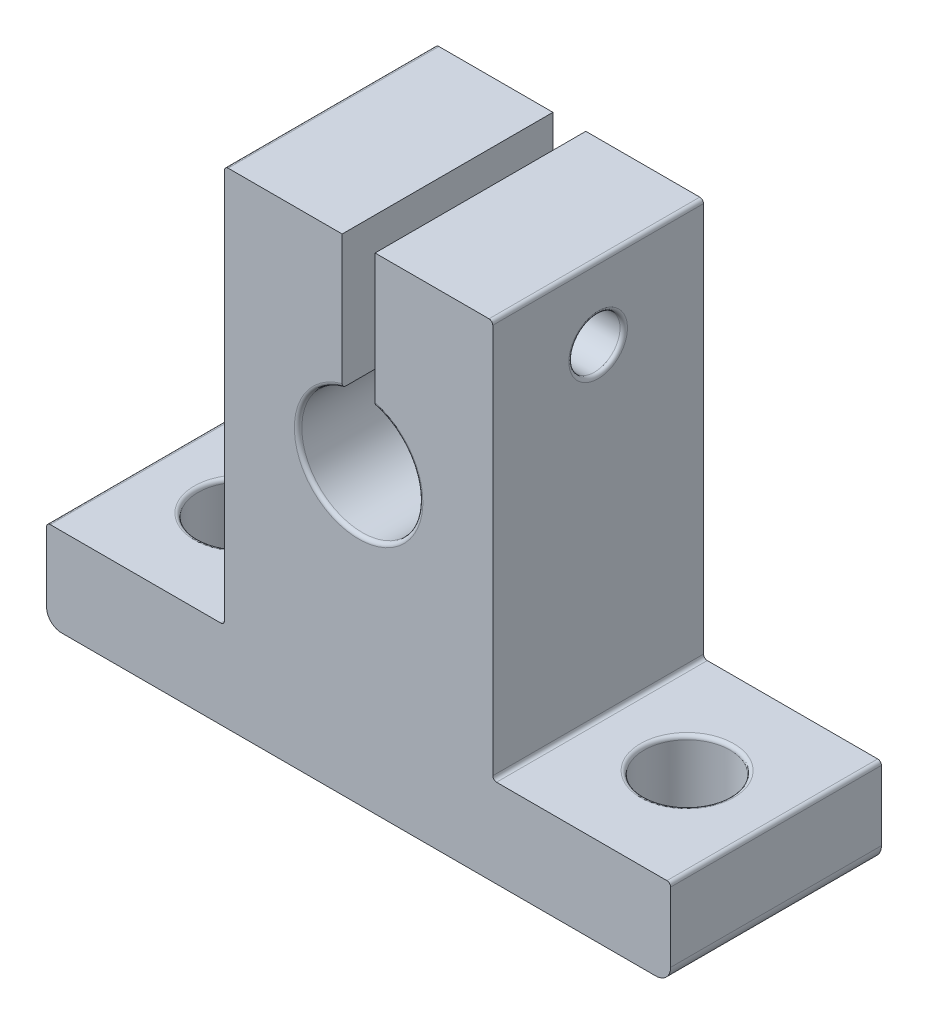
SolidWorks part; units mm, degrees
ref_plane "Front Plane" through (0, 0, 0) normal (0, 0, 1) x (1, 0, 0)
ref_plane "Top Plane" through (0, 0, 0) normal (0, 1, 0) x (1, 0, 0)
ref_plane "Right Plane" through (0, 0, 0) normal (1, 0, 0) x (0, 0, -1)
sketch "Sketch1" plane through (0, 0, 0) normal (0, 0, 1) x (1, 0, 0)
  line L0 (-20.875, 0) -> (20.875, 0)
  line L1 (20.875, 0) -> (20.875, 5.9)
  line L2 (20.875, 5.9) -> (8.975, 5.9)
  line L3 (8.975, 5.9) -> (8.975, 32.5)
  line L4 (8.975, 32.5) -> (1.1, 32.5)
  line L5 (1.1, 32.5) -> (1.1, 23.5728)
  line L6 (0, 0) -> (0, 19.675) construction
  line L7 (-1.1, 32.5) -> (-1.1, 23.5728)
  line L8 (-8.975, 32.5) -> (-1.1, 32.5)
  line L9 (-8.975, 5.9) -> (-8.975, 32.5)
  line L10 (-20.875, 5.9) -> (-8.975, 5.9)
  line L11 (-20.875, 0) -> (-20.875, 5.9)
  arc A0 (-1.1, 23.5728) -> (1.1, 23.5728) centre (0, 19.675) ccw
  dimension "D7" = 11.9
  dimension "D5" = 4.05
  dimension "D1" = 20.875
  dimension "D2" = 5.9
  dimension "D3" = 32.5
  dimension "D4" = 7.875
  dimension "D6" = 19.675
  dimension "D8" = 8.9272
  dimension "D9" = 1.1
extrude "Boss-Extrude1" add sketch "Sketch1" along normal mid plane 14.1
sketch "Sketch2" plane through (0, 5.9, 0) normal (0, 1, 0) x (1, 0, 0)
  line L0 (20.875, 0) -> (14.925, 0) construction
  line L1 (20.875, -7.05) -> (20.875, 7.05) construction
  line L2 (0, -55) -> (0, 55) construction
  circle A0 centre (14.925, 0) radius 2.875
  circle A1 centre (-14.925, 0) radius 2.875
  dimension "D2" = 5.75
  dimension "D1" = 5.95
extrude "Mounting Holes" cut sketch "Sketch2" against normal up to next
sketch "Sketch3" plane through (8.975, 0, 0) normal (1, 0, 0) x (0, 0, -1)
  line L0 (0, 32.5) -> (0, 27.59) construction
  line L1 (-7.05, 32.5) -> (7.05, 32.5) construction
  circle A0 centre (0, 27.59) radius 1.71
  dimension "D2" = 3.42
  dimension "D1" = 4.91
extrude "Bolt Hole" cut sketch "Sketch3" against normal through all
sketch "Sketch4" plane through (-8.975, 0, 0) normal (-1, 0, 0) x (0, 0, 1)
  circle A0 centre (0, 27.59) radius 3.675
  dimension "D1" = 7.35
extrude "Bolt Head" cut sketch "Sketch4" against normal blind 3.95
fillet "Holes" radius 0.25 5 edges at (8.975, 27.59, -1.71) (-12.05, 5.9, 0) (12.05, 5.9, 0) (0, 15.625, 7.05) (0, 15.625, -7.05)
sketch "Sketch5" plane through (-8.975, 0, 0) normal (-1, 0, 0) x (0, 0, 1)
  circle A5 centre (0, 27.59) radius 4.075
  circle A6 centre (0, 27.59) radius 4.075
  dimension "D1" = 0.4
extrude "Bolt Head Int Fillet" cut sketch "Sketch5" against normal blind 0.5 draft 45
fillet "Bottom Mounting" radius 0.5 2 edges at (14.925, 0, 2.875) (-14.925, 0, 2.875)
fillet "Bottom Corners" radius 1 2 edges at (20.875, 0, 0) (-20.875, 0, 0)
fillet "Corners" radius 0.25 6 edges at (8.975, 32.5, 0) (-8.975, 32.5, 0) (20.875, 5.9, 0) (8.975, 5.9, 0) (-8.975, 5.9, 0) (-20.875, 5.9, 0)
